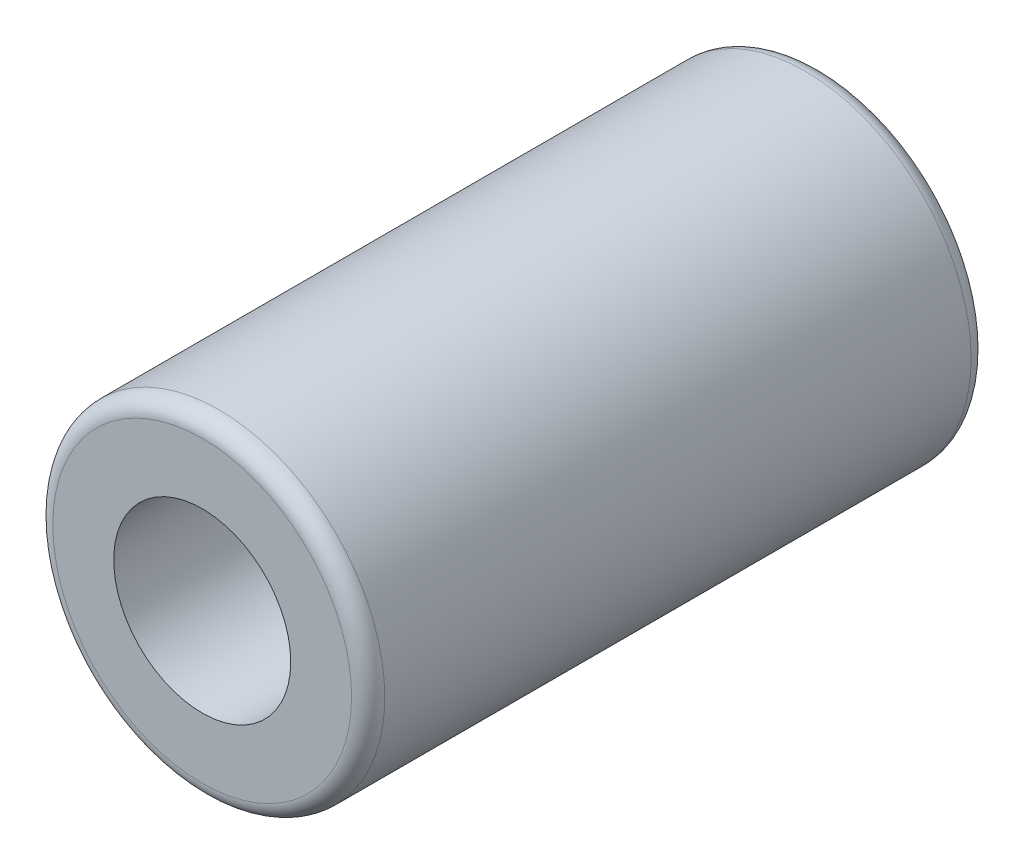
SolidWorks part; units mm, degrees
ref_plane "Front Plane" through (0, 0, 0) normal (0, 0, 1) x (1, 0, 0)
ref_plane "Top Plane" through (0, 0, 0) normal (0, 1, 0) x (1, 0, 0)
ref_plane "Right Plane" through (0, 0, 0) normal (1, 0, 0) x (0, 0, -1)
sketch "Sketch1" plane through (0, 0, 0) normal (0, 0, 1) x (1, 0, 0)
  circle A0 centre (0, 0) radius 3
  circle A1 centre (0, 0) radius 1.6
  dimension "D1" = 6
  dimension "D2" = 3.2
extrude "Boss-Extrude1" add sketch "Sketch1" along normal blind 11.2
fillet "Fillet1" radius 0.3 2 edges at (3, 0, 0) (3, 0, 11.2)
